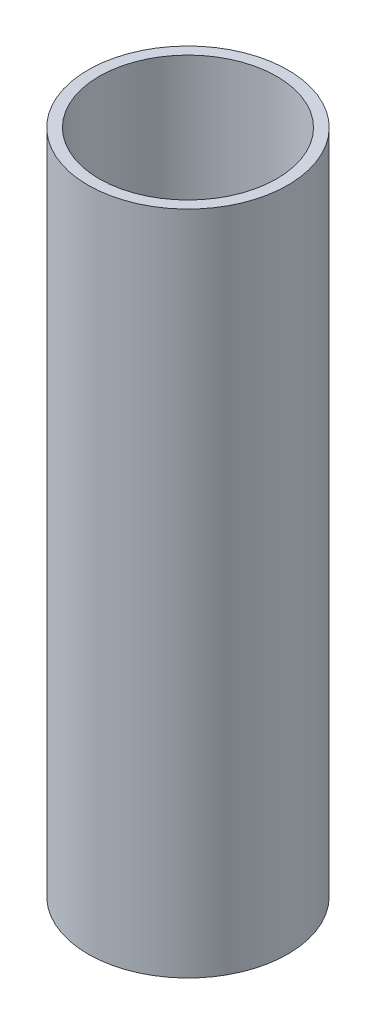
SolidWorks part; units mm, degrees
ref_plane "Front Plane" through (0, 0, 0) normal (0, 0, 1) x (1, 0, 0)
ref_plane "Top Plane" through (0, 0, 0) normal (0, 1, 0) x (1, 0, 0)
ref_plane "Right Plane" through (0, 0, 0) normal (1, 0, 0) x (0, 0, -1)
sketch "Sketch5" plane through (0, 0, 0) normal (0, 1, 0) x (1, 0, 0)
  circle A0 centre (0, 0) radius 40
  circle A1 centre (0, 0) radius 45
  dimension "D1" = 5
extrude "Boss-Extrude6" add sketch "Sketch5" along normal blind 300
